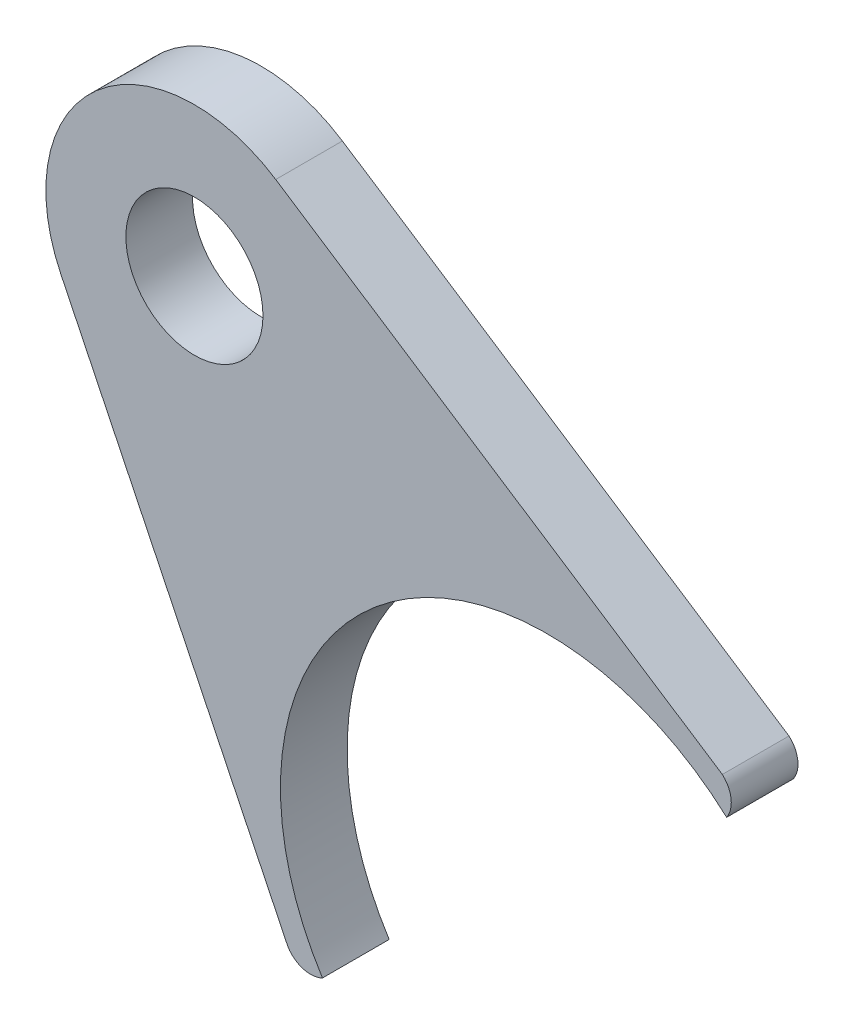
SolidWorks part; units mm, degrees
material "AISI 4340 Steel, annealed"
ref_plane "Front Plane" through (0, 0, 0) normal (0, 0, 1) x (1, 0, 0)
ref_plane "Top Plane" through (0, 0, 0) normal (0, 1, 0) x (1, 0, 0)
ref_plane "Right Plane" through (0, 0, 0) normal (1, 0, 0) x (0, 0, -1)
sketch "Sketch1" plane through (0, 0, 0) normal (0, 0, 1) x (1, 0, 0)
  line L0 (8.3328, 11.07) -> (-12.9296, 24.9708) construction
  line L1 (-12.3465, -6.379) -> (-23.1672, 15.967) construction
  line L2 (8.3328, 11.07) -> (-12.9296, 24.9708)
  line L3 (-12.3465, -6.379) -> (-23.1672, 15.967)
  arc A1 (8.5406, 9.4054) -> (8.3328, 11.07) centre (7.4904, 10.1196) ccw construction
  circle A2 centre (-16.8005, 19.05) radius 3.2639
  circle A3 centre (-16.8005, 19.05) radius 3.2639
  circle A4 centre (0, 0) radius 12.7045
  arc A5 (8.5406, 9.4054) -> (-10.7046, -6.8422) centre (0, 0) ccw
  arc A6 (-12.9296, 24.9708) -> (-23.1672, 15.967) centre (-16.8005, 19.05) ccw construction
  arc A7 (-12.3465, -6.379) -> (-10.7046, -6.8422) centre (-11.2701, -5.705) ccw construction
  arc A8 (8.5406, 9.4054) -> (8.3328, 11.07) centre (7.4904, 10.1196) ccw
  arc A9 (-12.9296, 24.9708) -> (-23.1672, 15.967) centre (-16.8005, 19.05) ccw
  arc A10 (-12.3465, -6.379) -> (-10.7046, -6.8422) centre (-11.2701, -5.705) ccw
  dimension "D1" = 0
  dimension "D2" = 0
extrude "Boss-Extrude1" add sketch "Sketch1" along normal blind 3.175
ref_point "Point2"
